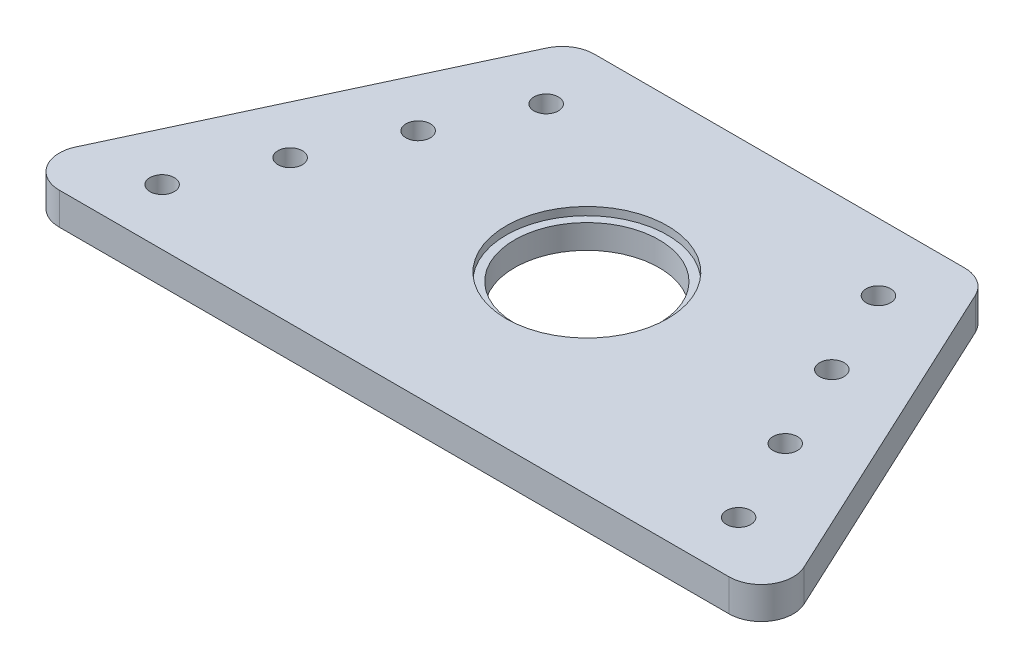
SolidWorks part; units mm, degrees
material "6061-T6 (SS)"
ref_plane "Front" through (0, 0, 0) normal (0, 0, 1) x (1, 0, 0)
ref_plane "Top" through (0, 0, 0) normal (0, 1, 0) x (1, 0, 0)
ref_plane "Right" through (0, 0, 0) normal (1, 0, 0) x (0, 0, -1)
sketch "Sketch1" plane through (0, 0, 0) normal (0, 1, 0) x (1, 0, 0)
  line L0 (-40.6674, 38.1) -> (40.6674, 38.1)
  line L1 (40.6674, 38.1) -> (76.2, -38.1)
  line L2 (76.2, -38.1) -> (-76.2, -38.1)
  line L3 (-76.2, -38.1) -> (-40.6674, 38.1)
  line L4 (0, 0) -> (0, 38.1) construction
  circle A0 centre (0, 0) radius 14.2875
  point P2 (0, 38.1)
  point P5 (0, -38.1)
  point P7 (-58.4337, 0)
  dimension "D1" = 28.575
  dimension "D3" = 65
  dimension "D2" = 38.1
  dimension "D4" = 152.4
extrude "Boss-Extrude1" add sketch "Sketch1" along normal blind 6.35
sketch "Sketch2" plane through (0, 6.35, 0) normal (0, 1, 0) x (1, 0, 0)
  line L0 (-40.6674, 38.1) -> (-76.2, -38.1) construction
  line L1 (-76.2, -38.1) -> (76.2, -38.1) construction
  line L2 (-57.0053, -26.9875) -> (-48.9544, -9.7223) construction
  line L3 (0, 0) -> (0, 38.1) construction
  line L4 (40.6674, 38.1) -> (-40.6674, 38.1) construction
  circle A0 centre (-57.0053, -26.9875) radius 2.413
  circle A1 centre (-48.9544, -9.7223) radius 2.413
  circle A2 centre (-40.9035, 7.5428) radius 2.413
  circle A3 centre (-32.8526, 24.808) radius 2.413
  circle A4 centre (32.8526, 24.808) radius 2.413
  circle A5 centre (40.9035, 7.5428) radius 2.413
  circle A6 centre (48.9544, -9.7223) radius 2.413
  circle A7 centre (57.0053, -26.9875) radius 2.413
  dimension "D1" = 4.826
  dimension "D2" = 12.7
  dimension "D3" = 11.1125
  dimension "D5" = 19.05
  dimension "D4" = 4
extrude "Cut-Extrude1" cut sketch "Sketch2" against normal through all
fillet "Fillet1" radius 6.35 4 edges at (-76.2, 3.175, 38.1) (-40.6674, 3.175, -38.1) (40.6674, 3.175, -38.1) (76.2, 3.175, 38.1)
sketch "Sketch3" plane through (0, 6.35, 0) normal (0, 1, 0) x (1, 0, 0)
  circle A0 centre (0, 0) radius 15.9385
  dimension "D1" = 31.877
extrude "Cut-Extrude2" cut sketch "Sketch3" against normal blind 1.5875
